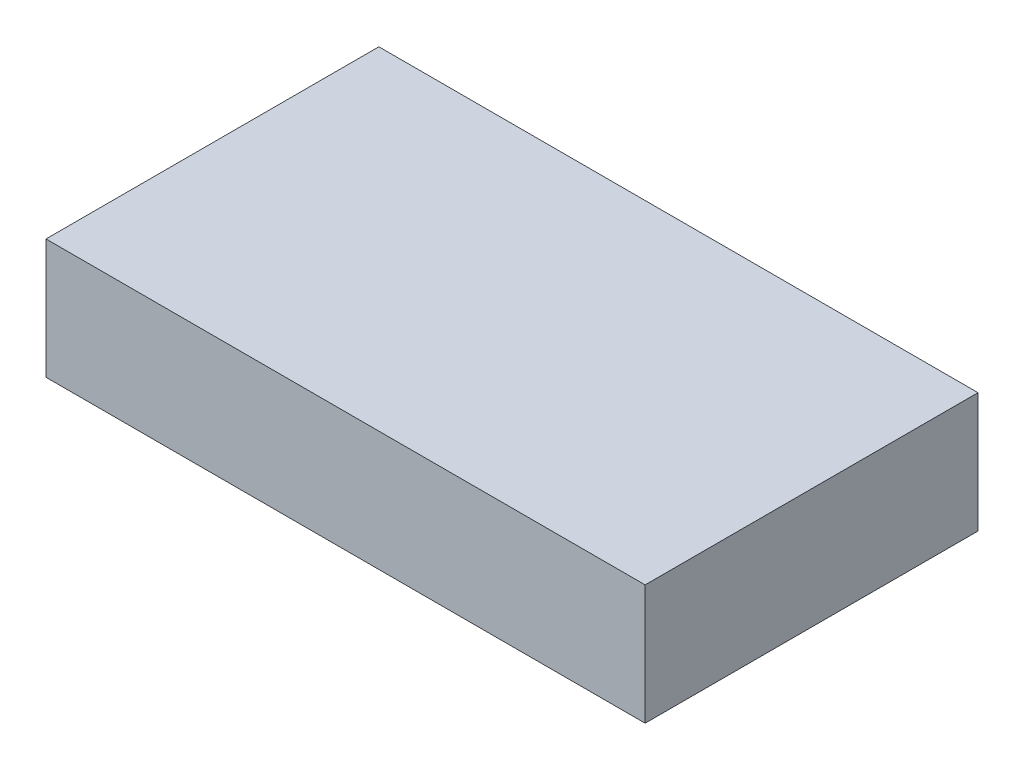
SolidWorks part; units mm, degrees
ref_plane "Front Plane" through (0, 0, 0) normal (0, 0, 1) x (1, 0, 0)
ref_plane "Top Plane" through (0, 0, 0) normal (0, 1, 0) x (1, 0, 0)
ref_plane "Right Plane" through (0, 0, 0) normal (1, 0, 0) x (0, 0, -1)
sketch "Sketch1" plane through (0, 0, 0) normal (0, 1, 0) x (1, 0, 0)
  line L1 (-22.5, 12.5) -> (22.5, 12.5)
  line L2 (-22.5, 12.5) -> (-22.5, -12.5)
  line L3 (-22.5, -12.5) -> (22.5, -12.5)
  line L4 (22.5, 12.5) -> (22.5, -12.5)
  line L5 (-22.5, 12.5) -> (22.5, -12.5) construction
  line L6 (-22.5, -12.5) -> (22.5, 12.5) construction
  point P0 (0, 0)
  dimension "D1" = 25
  dimension "D2" = 45
extrude "Boss-Extrude1" add sketch "Sketch1" along normal blind 9
